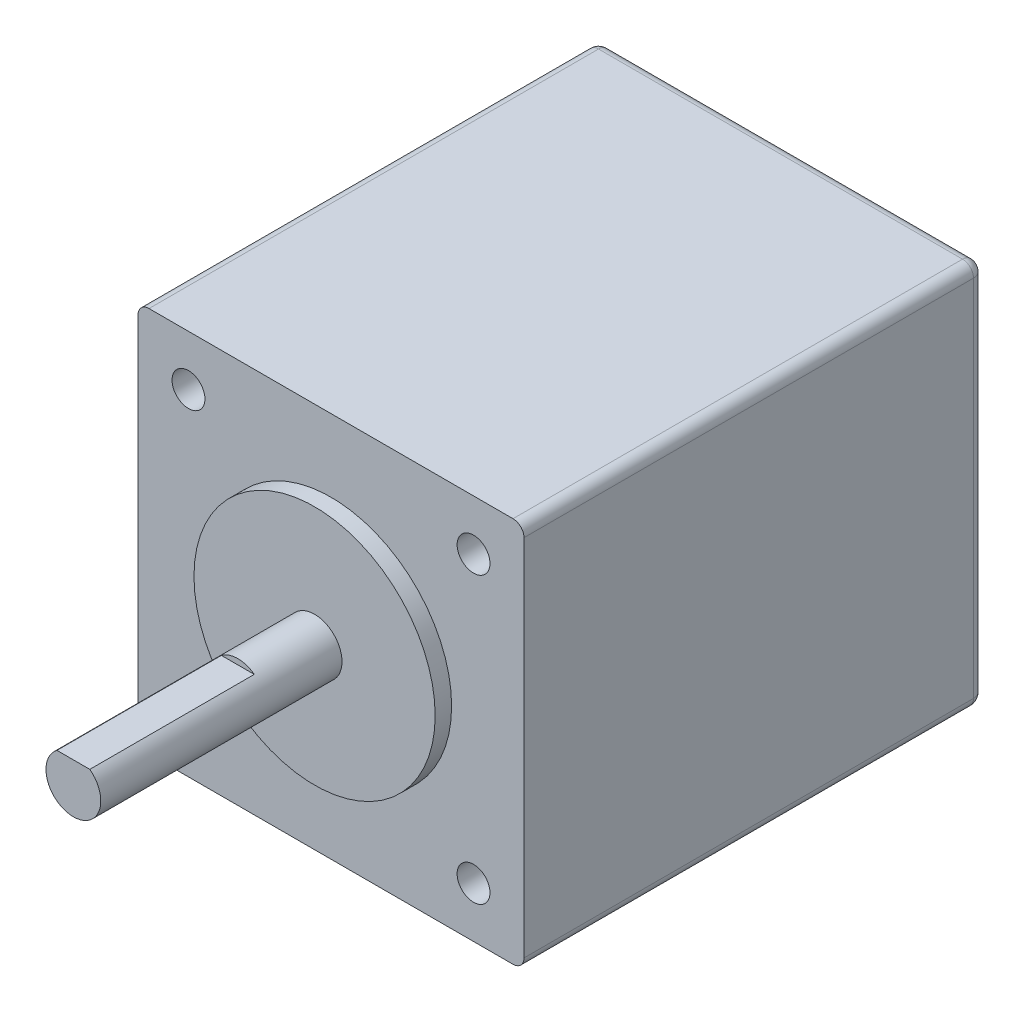
SolidWorks part; units mm, degrees
ref_plane "Front Plane" through (0, 0, 0) normal (0, 0, 1) x (1, 0, 0)
ref_plane "Top Plane" through (0, 0, 0) normal (0, 1, 0) x (1, 0, 0)
ref_plane "Right Plane" through (0, 0, 0) normal (1, 0, 0) x (0, 0, -1)
sketch "Sketch1" plane through (0, 0, 0) normal (0, 0, 1) x (1, 0, 0)
  line L1 (-17.6, -17.6) -> (17.6, -17.6)
  line L2 (-17.6, -17.6) -> (-17.6, 17.6)
  line L3 (-17.6, 17.6) -> (17.6, 17.6)
  line L4 (17.6, -17.6) -> (17.6, 17.6)
  line L5 (-17.6, -17.6) -> (17.6, 17.6) construction
  line L6 (-17.6, 17.6) -> (17.6, -17.6) construction
  point P0 (0, 0)
  dimension "D1" = 35.2
  dimension "D2" = 35.2
extrude "Boss-Extrude1" add sketch "Sketch1" along normal blind 42
sketch "Sketch2" plane through (0, 0, 42) normal (0, 0, 1) x (1, 0, 0)
  circle A0 centre (0, 0) radius 11
  dimension "D1" = 22
extrude "Boss-Extrude2" add sketch "Sketch2" along normal blind 1.5
sketch "Sketch3" plane through (0, 0, 43.5) normal (0, 0, 1) x (1, 0, 0)
  circle A0 centre (0, 0) radius 2.5
  dimension "D1" = 5
extrude "Boss-Extrude3" add sketch "Sketch3" along normal blind 22
sketch "Sketch4" plane through (0, 0, 0) normal (1, 0, 0) x (0, 0, -1)
  line L1 (-65.5, 2.5) -> (-50.5, 2.5)
  line L2 (-65.5, 2.5) -> (-65.5, 2)
  line L3 (-65.5, 2) -> (-50.5, 2)
  line L4 (-50.5, 2.5) -> (-50.5, 2)
  dimension "D1" = 15
  dimension "D2" = 0.5
extrude "Cut-Extrude1" cut sketch "Sketch4" against normal mid plane 10
sketch "Sketch5" plane through (0, 0, 42) normal (0, 0, 1) x (1, 0, 0)
  line L1 (-13, -13) -> (13, -13) construction
  line L2 (-13, -13) -> (-13, 13) construction
  line L3 (-13, 13) -> (13, 13) construction
  line L4 (13, -13) -> (13, 13) construction
  line L5 (-13, -13) -> (13, 13) construction
  line L6 (-13, 13) -> (13, -13) construction
  circle A0 centre (-13, 13) radius 1.5
  circle A1 centre (13, 13) radius 1.5
  circle A2 centre (13, -13) radius 1.5
  circle A3 centre (-13, -13) radius 1.5
  point P0 (0, 0)
  dimension "D3" = 3
  dimension "D1" = 26
  dimension "D2" = 26
  dimension "D4" = 4
extrude "Cut-Extrude2" cut sketch "Sketch5" against normal blind 4.5
fillet "Fillet1" radius 1 8 edges at (0, 17.6, 0) (-17.6, 0, 0) (0, -17.6, 0) (17.6, 0, 0) (-17.6, -17.6, 21) (17.6, -17.6, 21) (-17.6, 17.6, 21) (17.6, 17.6, 21)
